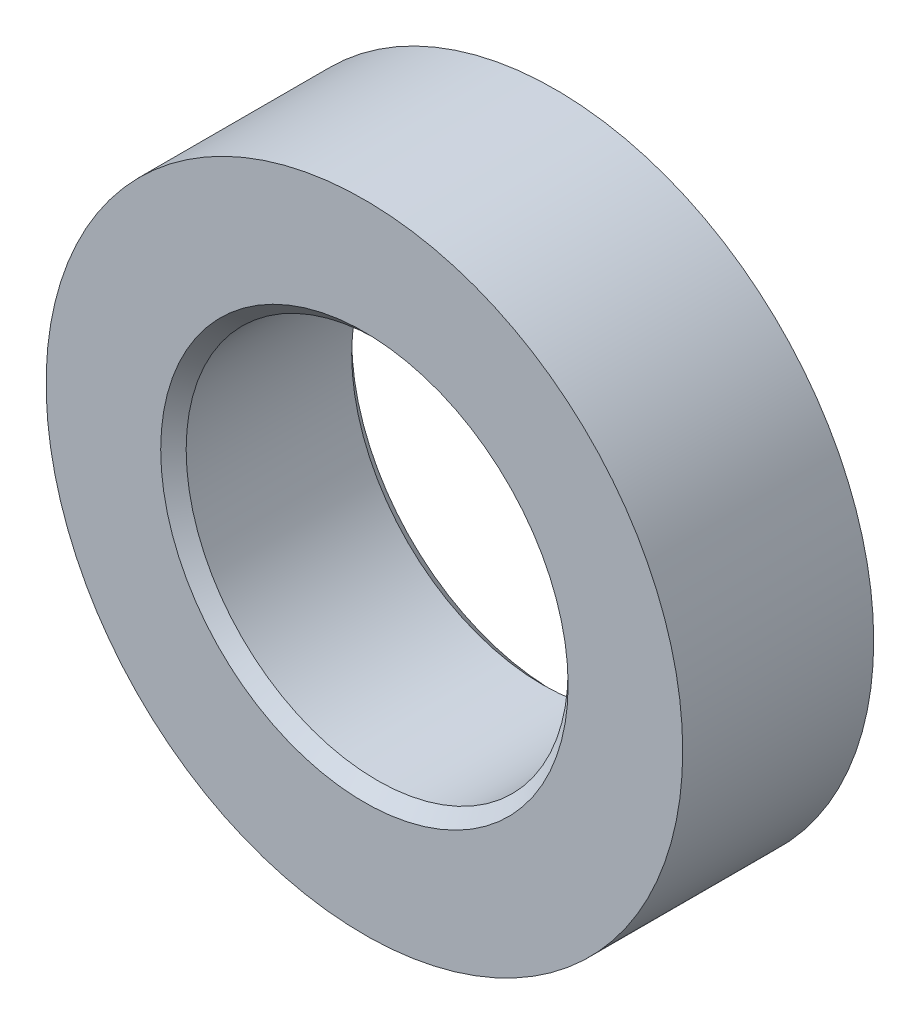
SolidWorks part; units mm, degrees
material "AISI 321 Annealed Stainless Steel (SS)"
ref_plane "Front Plane" through (0, 0, 0) normal (0, 0, 1) x (1, 0, 0)
ref_plane "Top Plane" through (0, 0, 0) normal (0, 1, 0) x (1, 0, 0)
ref_plane "Right Plane" through (0, 0, 0) normal (1, 0, 0) x (0, 0, -1)
sketch "Sketch1" plane through (0, 0, 0) normal (0, 0, 1) x (1, 0, 0)
  circle A0 centre (0, 0) radius 25
  circle A1 centre (0, 0) radius 15
  dimension "D1" = 30
  dimension "D2" = 50
extrude "Boss-Extrude1" add sketch "Sketch1" along normal blind 15
chamfer "Chamfer1" distance 1 angle 45 2 edges at (15, 0, 0) (15, 0, 15)
